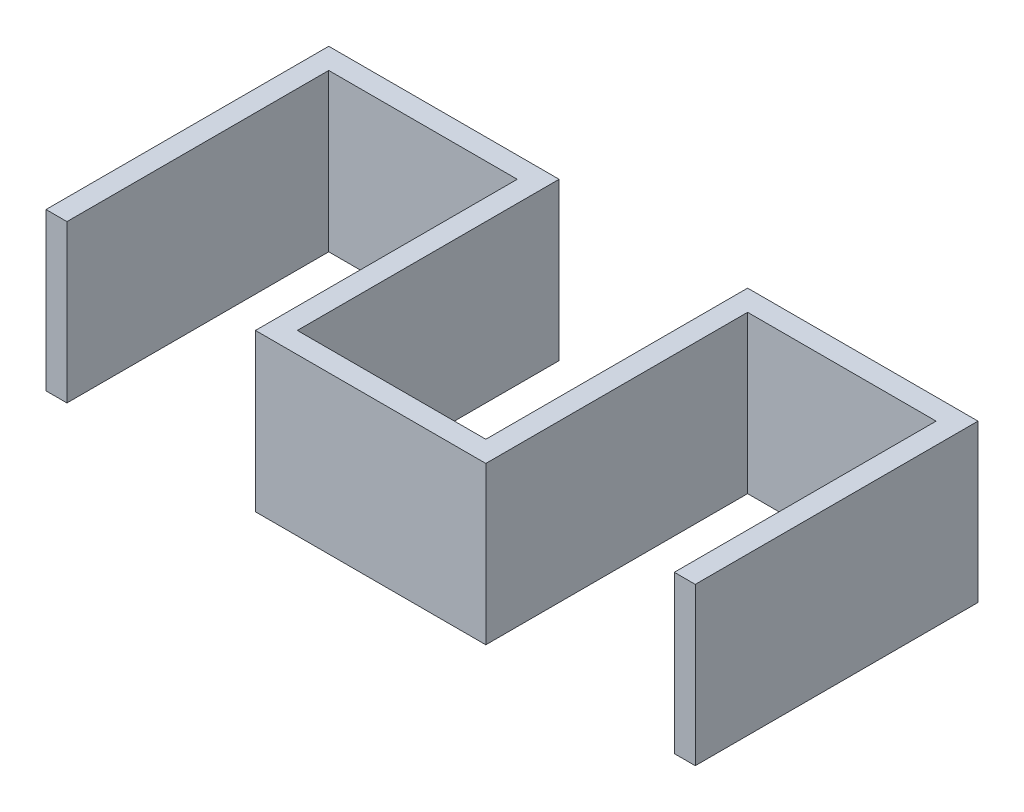
SolidWorks part; units mm, degrees
ref_plane "Front Plane" through (0, 0, 0) normal (0, 0, 1) x (1, 0, 0)
ref_plane "Top Plane" through (0, 0, 0) normal (0, 1, 0) x (1, 0, 0)
ref_plane "Right Plane" through (0, 0, 0) normal (1, 0, 0) x (0, 0, -1)
sketch "Sketch1" plane through (0, 0, 0) normal (0, 1, 0) x (1, 0, 0)
  line L0 (0, 0) -> (0, 25)
  line L1 (0, 25) -> (18, 25)
  line L2 (18, 25) -> (18, 0)
  line L3 (18, 0) -> (40, 0)
  line L4 (40, 0) -> (40, 25)
  line L5 (40, 25) -> (58, 25)
  line L6 (58, 25) -> (58, 0)
  dimension "D1" = 25
  dimension "D2" = 22
  dimension "20" = 18
extrude "Extrude-Thin1" add sketch "Sketch1" along normal blind 15 thin thin type one direction reverse wall 2
